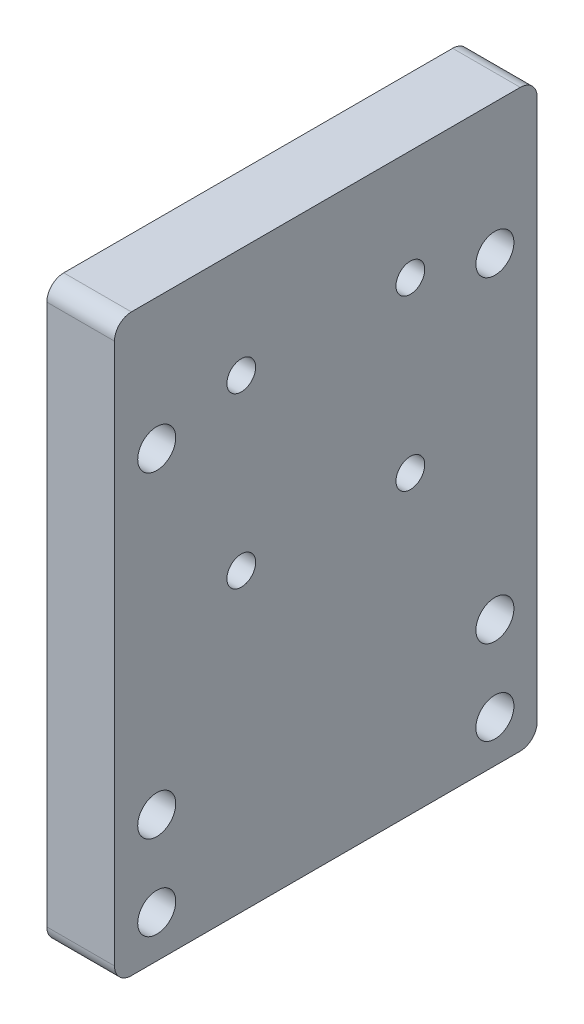
SolidWorks part; units mm, degrees
material "6061-T6 (SS)"
ref_plane "Front Plane" through (0, 0, 0) normal (0, 0, 1) x (1, 0, 0)
ref_plane "Top Plane" through (0, 0, 0) normal (0, 1, 0) x (1, 0, 0)
ref_plane "Right Plane" through (0, 0, 0) normal (1, 0, 0) x (0, 0, -1)
sketch "Sketch1" plane through (0, 0, 0) normal (1, 0, 0) x (0, 0, -1)
  line L1 (-25, -34) -> (25, -34)
  line L2 (-25, -34) -> (-25, 34)
  line L3 (-25, 34) -> (25, 34)
  line L4 (25, -34) -> (25, 34)
  line L5 (-25, -34) -> (25, 34) construction
  line L6 (-25, 34) -> (25, -34) construction
  point P0 (0, 0)
  dimension "D1" = 50
  dimension "D2" = 68
extrude "Boss-Extrude1" add sketch "Sketch1" along normal blind 8
hole_wizard "M3 Clearance Hole1" positions "Sketch2" profile "Sketch3" hole size "M3" standard "ISO" end condition through all
sketch "Sketch2" plane through (8, 0, 0) normal (1, 0, 0) x (0, 0, -1)
  line L1 (-10, 1) -> (10, 1) construction
  line L2 (-10, 1) -> (-10, 21) construction
  line L3 (-10, 21) -> (10, 21) construction
  line L4 (10, 1) -> (10, 21) construction
  line L5 (-10, 1) -> (10, 21) construction
  line L6 (-10, 21) -> (10, 1) construction
  line L8 (0, 21) -> (0, 1) construction
  line L9 (-25, -34) -> (25, -34) construction
  point P0 (-10, 21)
  point P2 (10, 21)
  point P4 (10, 1)
  point P6 (-10, 1)
  dimension "D1" = 20
  dimension "D2" = 35
sketch "Sketch3" plane through (8, 21, 10) normal (0, 1, 0) x (0, 0, -1)
  line L0 (0, 0) -> (0, 8)
  line L1 (0, 8) -> (1.7, 8)
  line L2 (1.7, 8) -> (1.7, 0)
  line L5 (1.7, 0) -> (0, 0)
  line L11 (0, -6.35) -> (0, 107.95) construction
  dimension "Thru Hole Dia." = 3.4
  dimension "Thru Hole Depth" = 8
hole_wizard "CSK for M4 Hex Socket Countersunk Cap Screw1" positions "Sketch4" profile "Sketch6" countersink size "M4" standard "ISO" end condition through all
sketch "Sketch4" plane through (0, 0, 0) normal (-1, 0, 0) x (0, 0, 1)
  line L0 (-25, -34) -> (-25, 34) construction
  line L1 (25, -34) -> (-25, -34) construction
  line L2 (-20, -29) -> (-20, -34) construction
  line L4 (-20, -29) -> (-25, -29) construction
  line L6 (20, -29) -> (25, -29) construction
  line L7 (25, 34) -> (25, -34) construction
  line L9 (20, -29) -> (20, -34) construction
  point P0 (-20, -29)
  point P2 (20, -29)
  dimension "D1" = 5
sketch "Sketch6" plane through (0, -29, -20) normal (0, 1, 0) x (0, 0, 1)
  line L0 (0, 0) -> (0, 8)
  line L1 (0, 8) -> (2.25, 8)
  line L2 (2.25, 8) -> (2.25, 2.23)
  line L3 (2.25, 2.23) -> (4.48, 0)
  line L5 (4.48, 0) -> (0, 0)
  line L6 (-2.25, 2.23) -> (-4.48, 0) construction
  line L11 (0, -6.35) -> (0, 107.95) construction
  dimension "Thru Hole Dia." = 4.5
  dimension "Thru Hole Depth" = 8
  dimension "Near C'Sink Dia." = 8.96
  dimension "Near C'Sink Angle" = 90
fillet "Fillet1" radius 2 4 edges at (4, -34, -25) (4, -34, 25) (4, 34, -25) (4, 34, 25)
sketch "Sketch7" plane through (0, 0, 0) normal (-1, 0, 0) x (0, 0, 1)
  line L0 (25, 32) -> (25, -32) construction
  line L1 (-20, 18.5) -> (20, 18.5)
  line L2 (-20, 18.5) -> (-20, -19)
  line L3 (-20, -19) -> (20, -19)
  line L4 (20, 18.5) -> (20, -19)
  line L5 (23, -34) -> (-23, -34) construction
  point P6 (0, 18.5)
  dimension "D1" = 5
  dimension "D2" = 15
  dimension "D3" = 37.5
hole_wizard "CSK for M4 Hex Socket Countersunk Cap Screw2" positions "Sketch8" profile "Sketch9" countersink size "M4" standard "ISO" end condition through all
sketch "Sketch8" plane through (0, 0, 0) normal (-1, 0, 0) x (0, 0, 1)
  point P0 (20, -19)
  point P3 (20, 18.5)
  point P6 (-20, 18.5)
  point P9 (-20, -19)
sketch "Sketch9" plane through (0, -19, 20) normal (0, 1, 0) x (0, 0, 1)
  line L0 (0, 0) -> (0, 8)
  line L1 (0, 8) -> (2.25, 8)
  line L2 (2.25, 8) -> (2.25, 2.23)
  line L3 (2.25, 2.23) -> (4.48, 0)
  line L5 (4.48, 0) -> (0, 0)
  line L6 (-2.25, 2.23) -> (-4.48, 0) construction
  line L11 (0, -6.35) -> (0, 107.95) construction
  dimension "Thru Hole Dia." = 4.5
  dimension "Thru Hole Depth" = 8
  dimension "Near C'Sink Dia." = 8.96
  dimension "Near C'Sink Angle" = 90
